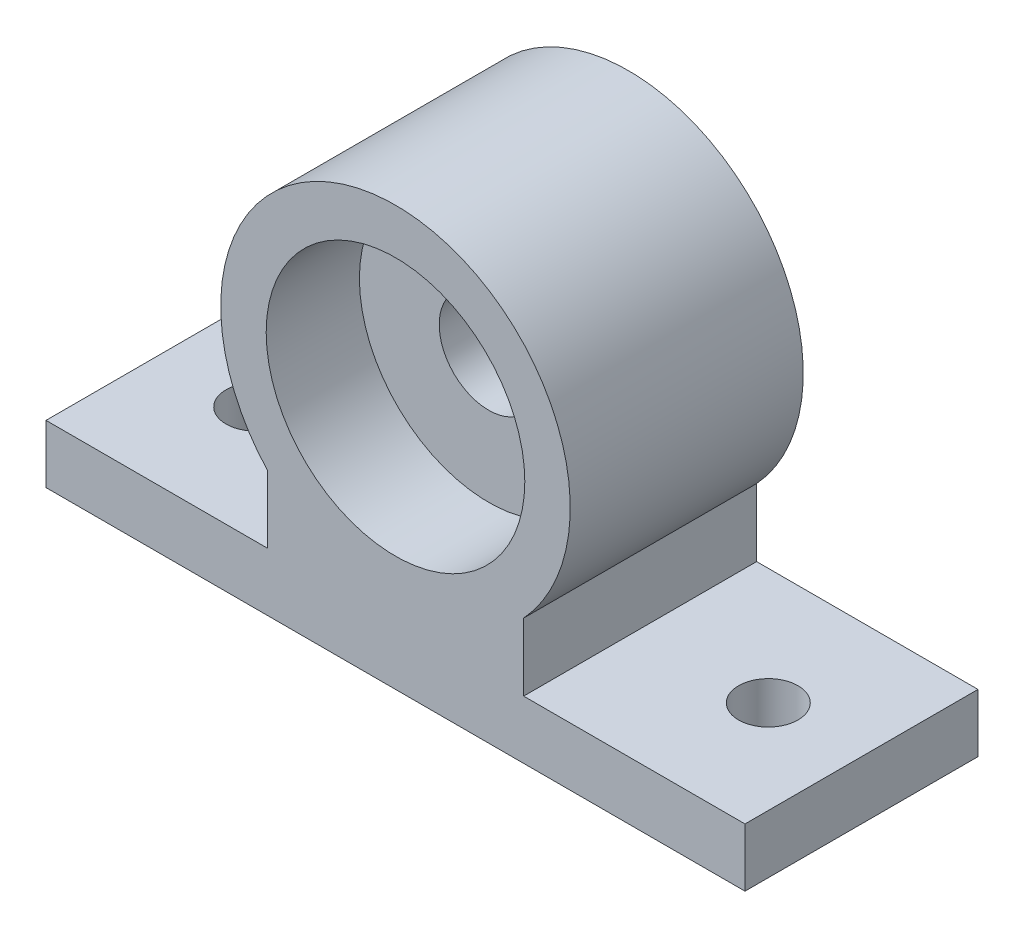
SolidWorks part; units mm, degrees
ref_plane "前视基准面" through (0, 0, 0) normal (0, 0, 1) x (1, 0, 0)
ref_plane "上视基准面" through (0, 0, 0) normal (0, 1, 0) x (1, 0, 0)
ref_plane "右视基准面" through (0, 0, 0) normal (1, 0, 0) x (0, 0, -1)
sketch "草图1" plane through (0, 0, 0) normal (0, 1, 0) x (1, 0, 0)
  line L1 (-20.0524, 5.4974) -> (39.9476, 5.4974)
  line L2 (-20.0524, 5.4974) -> (-20.0524, -14.5026)
  line L3 (-20.0524, -14.5026) -> (39.9476, -14.5026)
  line L4 (39.9476, 5.4974) -> (39.9476, -14.5026)
  circle A0 centre (-12.0524, -4.5026) radius 2.55
  circle A1 centre (31.9476, -4.5026) radius 2.55
  dimension "D3" = 5.1
  dimension "D4" = 5.1
  dimension "D5" = 8
  dimension "D6" = 8
  dimension "D1" = 20
  dimension "D2" = 60
extrude "凸台-拉伸1" add sketch "草图1" along normal blind 5
sketch "草图3" plane through (0, 5, 0) normal (0, 1, 0) x (1, 0, 0)
  line L0 (39.9476, 5.4974) -> (-20.0524, 5.4974) construction
  line L1 (-1.0524, 5.4974) -> (20.9476, 5.4974)
  line L2 (-1.0524, 5.4974) -> (-1.0524, -14.5026)
  line L3 (-1.0524, -14.5026) -> (20.9476, -14.5026)
  line L4 (20.9476, 5.4974) -> (20.9476, -14.5026)
  line L5 (-20.0524, -14.5026) -> (39.9476, -14.5026) construction
  line L6 (39.9476, -14.5026) -> (39.9476, 5.4974) construction
  dimension "D1" = 22
  dimension "D2" = 19
extrude "凸台-拉伸2" add sketch "草图3" along normal blind 16
sketch "草图4" plane through (0, 0, -5.4974) normal (0, 0, -1) x (-1, 0, 0)
  line L0 (-20.9476, 21) -> (1.0524, 21) construction
  circle A0 centre (-9.9476, 21) radius 15
  dimension "D1" = 30
extrude "凸台-拉伸3" add sketch "草图4" against normal up to surface (20 mm away) up to face at (9.9476, 7.75, 14.5026)
sketch "草图5" plane through (0, 0, 14.5026) normal (0, 0, 1) x (1, 0, 0)
  circle A0 centre (9.9476, 21) radius 4.25
  dimension "D1" = 8.5
extrude "切除-拉伸1" cut sketch "草图5" against normal through all
sketch "草图6" plane through (0, 0, 14.5026) normal (0, 0, 1) x (1, 0, 0)
  circle A0 centre (9.9476, 21) radius 11.1
  dimension "D1" = 22.2
extrude "切除-拉伸2" cut sketch "草图6" against normal blind 8
